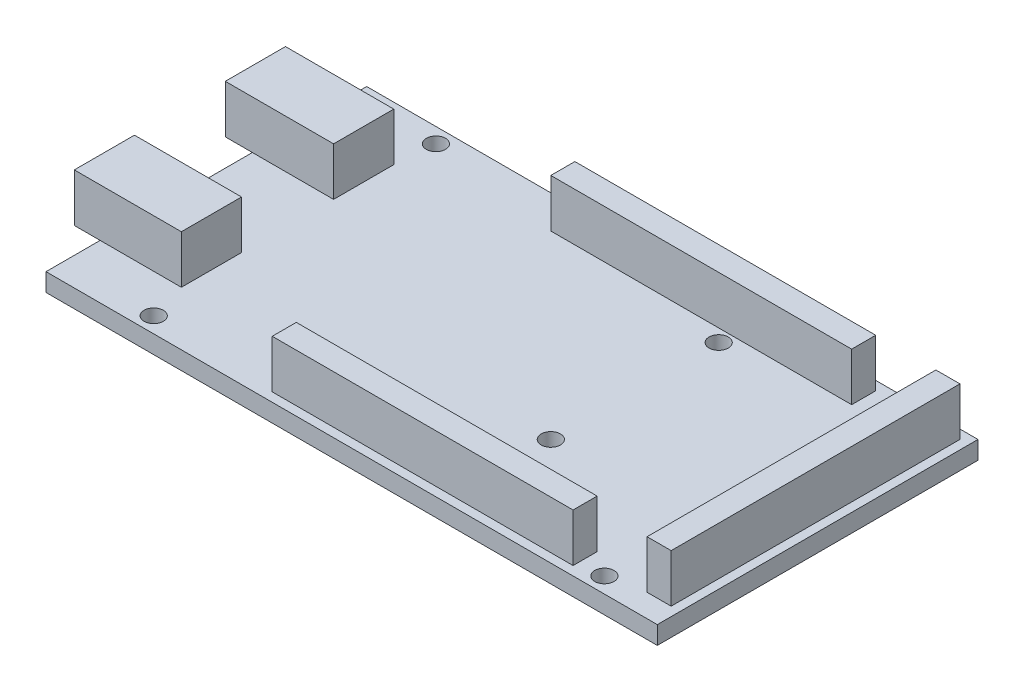
SolidWorks part; units mm, degrees
ref_plane "Front Plane" through (0, 0, 0) normal (0, 0, 1) x (1, 0, 0)
ref_plane "Top Plane" through (0, 0, 0) normal (0, 1, 0) x (1, 0, 0)
ref_plane "Right Plane" through (0, 0, 0) normal (1, 0, 0) x (0, 0, -1)
sketch "Sketch1" plane through (0, 0, 0) normal (0, 1, 0) x (1, 0, 0)
  line L1 (0, 0) -> (101.6, 0)
  line L2 (0, 0) -> (0, 53.3)
  line L3 (0, 53.3) -> (101.6, 53.3)
  line L4 (101.6, 0) -> (101.6, 53.3)
  dimension "D1" = 101.6
  dimension "D2" = 53.3
extrude "Boss-Extrude1" add sketch "Sketch1" along normal blind 3
sketch "Sketch2" plane through (0, 3, 0) normal (0, 1, 0) x (1, 0, 0)
  line L0 (0, 0) -> (101.6, 0) construction
  line L5 (36.1, 51.8) -> (86.1, 51.8)
  line L6 (36.1, 51.8) -> (36.1, 47.8)
  line L7 (36.1, 47.8) -> (86.1, 47.8)
  line L8 (86.1, 51.8) -> (86.1, 47.8)
  line L9 (96.1, 51.8) -> (100.1, 51.8)
  line L10 (96.1, 51.8) -> (96.1, 3.8)
  line L11 (96.1, 3.8) -> (100.1, 3.8)
  line L12 (100.1, 51.8) -> (100.1, 3.8)
  line L13 (36.1, 5.5) -> (86.1, 5.5)
  line L14 (36.1, 5.5) -> (36.1, 1.5)
  line L15 (36.1, 1.5) -> (86.1, 1.5)
  line L16 (86.1, 5.5) -> (86.1, 1.5)
  line L17 (101.6, 53.3) -> (0, 53.3) construction
  line L19 (101.6, 0) -> (101.6, 53.3) construction
  line L36 (0, 53.3) -> (0, 0) construction
  line L37 (-4.5, 44.3) -> (13.5, 44.3)
  line L38 (-4.5, 44.3) -> (-4.5, 34.3)
  line L39 (-4.5, 34.3) -> (13.5, 34.3)
  line L40 (13.5, 44.3) -> (13.5, 34.3)
  line L41 (-4.2962, 19) -> (13.5, 19)
  line L42 (-4.2962, 19) -> (-4.2962, 9)
  line L43 (-4.2962, 9) -> (13.5, 9)
  line L44 (13.5, 19) -> (13.5, 9)
  point P22 (98.1, 51.8)
  point P29 (-4.5, 39.3)
  dimension "D1" = 1.5
  dimension "D2" = 1.5
  dimension "D3" = 10
  dimension "D4" = 9
  dimension "D5" = 48
  dimension "D6" = 50
  dimension "D7" = 10
  dimension "D8" = 4
  dimension "D9" = 1.5
  dimension "D10" = 9
  dimension "D11" = 4.5
  dimension "D12" = 18
extrude "Boss-Extrude2" add sketch "Sketch2" along normal blind 8
hole_wizard "M3 Clearance Hole1" positions "Sketch3" profile "Sketch4" hole size "M3" standard "ANSI Metric" end condition through all
sketch "Sketch3" plane through (0, 0, 0) normal (0, -1, 0) x (-1, 0, 0)
  line L0 (-14, 50.8) -> (-92.7, 50.8) construction
  line L2 (-15.3, 2.6) -> (-90.2, 2.6) construction
  line L4 (-66.1, 17.8) -> (-66.1, 45.7) construction
  line L6 (0, 53.3) -> (0, 0) construction
  line L7 (-101.6, 53.3) -> (0, 53.3) construction
  point P0 (-14, 50.8)
  point P2 (-66.1, 45.7)
  point P4 (-66.1, 17.8)
  point P6 (-92.7, 50.8)
  point P8 (-15.3, 2.6)
  point P10 (-90.2, 2.6)
  dimension "D1" = 14
  dimension "D2" = 1.3
  dimension "D3" = 50.8
  dimension "D4" = 24.1
  dimension "D5" = 2.5
  dimension "D6" = 5.1
  dimension "D7" = 27.9
  dimension "D8" = 15.2
  dimension "D9" = 2.5
sketch "Sketch4" plane through (14, 0, -50.8) normal (1, 0, 0) x (0, 0, -1)
  line L0 (0, 0) -> (0, 11)
  line L1 (0, 11) -> (1.6, 11)
  line L2 (1.6, 11) -> (1.6, 0)
  line L5 (1.6, 0) -> (0, 0)
  line L11 (0, -6.35) -> (0, 107.95) construction
  dimension "Thru Hole Dia." = 3.2
  dimension "Thru Hole Depth" = 11
